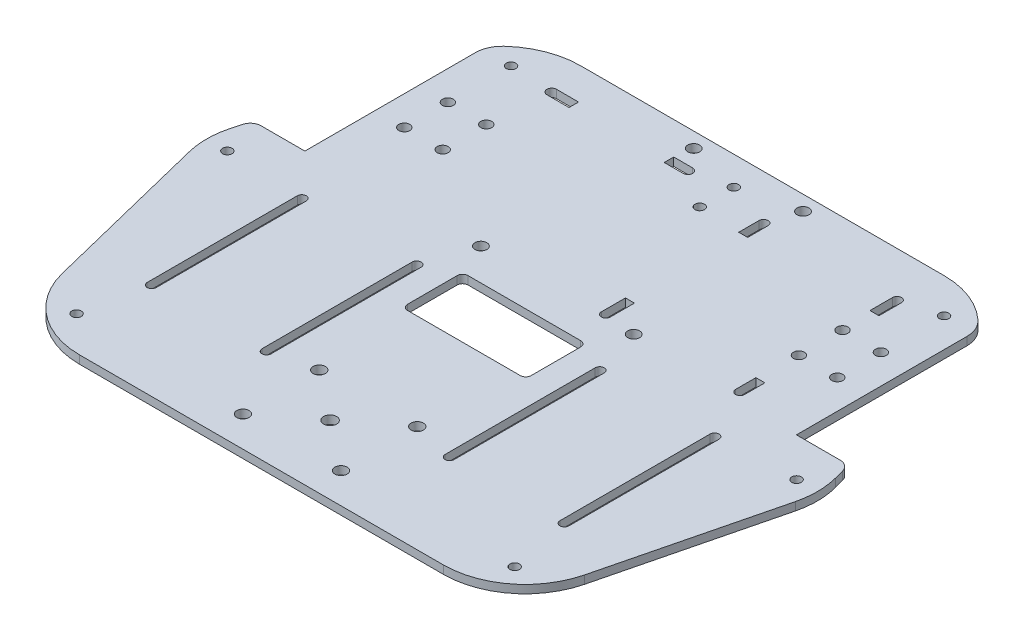
SolidWorks part; units mm, degrees
ref_plane "前视基准面" through (0, 0, 0) normal (0, 0, 1) x (1, 0, 0)
ref_plane "上视基准面" through (0, 0, 0) normal (0, 1, 0) x (1, 0, 0)
ref_plane "右视基准面" through (0, 0, 0) normal (1, 0, 0) x (0, 0, -1)
sketch "草图1" plane through (0, 0, 0) normal (0, 1, 0) x (1, 0, 0)
  line L0 (0, 115.8486) -> (0, -4.1514) construction
  line L1 (-90.25, 115.8486) -> (90.25, 115.8486) construction
  line L2 (96.25, 148.3486) -> (96.25, 83.3486) construction
  line L3 (90.25, 115.8486) -> (96.25, 115.8486) construction
  line L4 (-90.25, 115.8486) -> (-96.25, 115.8486) construction
  line L5 (-96.25, 148.3486) -> (-96.25, 83.3486) construction
  line L6 (90.25, 115.8486) -> (90.25, 131.8486)
  line L7 (95.8987, -6.5662) -> (111.2655, 55.4037)
  line L9 (-95.8987, -6.5662) -> (-111.2655, 55.4037)
  line L10 (137.9048, 62.6242) -> (-113.2043, 62.6242) construction
  line L11 (-90.25, 83.3486) -> (-90.25, 131.8486)
  line L12 (-66.7806, -29.3457) -> (66.7806, -29.3457)
  line L13 (90.25, 83.3486) -> (90.25, 76.8314)
  line L14 (-90.25, 83.3486) -> (-90.25, 76.8314)
  line L15 (-110.1941, 73.8661) -> (-111.1265, 70.3839)
  line L16 (90.25, 83.3486) -> (90.25, 115.8486)
  line L17 (110.1941, 73.8661) -> (111.1265, 70.3839)
  line L18 (106.3302, 76.8314) -> (90.25, 76.8314)
  line L19 (-90.25, 76.8314) -> (-106.3302, 76.8314)
  line L20 (0, 9.3997) -> (0, 129.3997) construction
  line L21 (-66.7806, 154.594) -> (66.7806, 154.594)
  line L22 (-90.25, 131.8486) -> (-90.25, 139.3783)
  line L23 (90.25, 131.8486) -> (90.25, 139.3783)
  arc A0 (95.8987, -6.5662) -> (66.7806, -29.3457) centre (66.7806, 0.6543) cw
  arc A1 (-66.7806, -29.3457) -> (-95.8987, -6.5662) centre (-66.7806, 0.6543) cw
  arc A2 (111.2655, 55.4037) -> (111.1265, 70.3839) centre (82.1474, 62.6242) ccw
  arc A3 (-111.1265, 70.3839) -> (-111.2655, 55.4037) centre (-82.1474, 62.6242) ccw
  circle A4 centre (0, -4.1514) radius 2.4148
  arc A5 (90.25, 139.3783) -> (86.9847, 146.7704) centre (80.25, 139.3783) ccw
  arc A6 (-66.7806, 154.594) -> (-86.9847, 146.7704) centre (-66.7806, 124.594) ccw
  arc A7 (86.9847, 146.7704) -> (66.7806, 154.594) centre (66.7806, 124.594) ccw
  arc A8 (-86.9847, 146.7704) -> (-90.25, 139.3783) centre (-80.25, 139.3783) ccw
  arc A9 (110.1941, 73.8661) -> (106.3302, 76.8314) centre (106.3302, 72.8314) ccw
  arc A10 (-106.3302, 76.8314) -> (-110.1941, 73.8661) centre (-106.3302, 72.8314) ccw
  point P6 (0, 115.8486)
  point P10 (96.25, 115.8486)
  point P18 (90.25, -29.3457)
  point P24 (-90.25, -29.3457)
  point P26 (0, 62.6242)
  point P28 (113.2043, 62.6242)
  point P51 (-90.25, 154.594)
  point P52 (90.25, 154.594)
  dimension "D5" = 30
  dimension "D6" = 30
  dimension "D8" = 10
  dimension "D9" = 4
  dimension "D1" = 180.5
  dimension "D2" = 120
  dimension "D3" = 65
  dimension "D4" = 6
  dimension "D7" = 16
extrude "凸台-拉伸1" add sketch "草图1" along normal blind 3
sketch "草图2" plane through (0, 3, 0) normal (0, 1, 0) x (1, 0, 0)
  line L0 (85.2655, -22.9742) -> (66.7806, 0.6543) construction
  line L1 (0, 85.1711) -> (0, 26.2624) construction
  line L2 (-85.2655, -22.9742) -> (-66.7806, 0.6543) construction
  arc A0 (66.7806, -29.3457) -> (95.8987, -6.5662) centre (66.7806, 0.6543) ccw construction
  circle A1 centre (80.4502, -16.819) radius 1.75
  circle A2 centre (104.5075, 62.6242) radius 1.75
  circle A3 centre (-104.5075, 62.6242) radius 1.75
  circle A4 centre (-80.4502, -16.819) radius 1.75
  dimension "D1" = 3.5
  dimension "D2" = 3.5
extrude "切除-拉伸1" cut sketch "草图2" against normal blind 10
sketch "草图3" plane through (0, 3, 0) normal (0, 1, 0) x (1, 0, 0)
  circle A0 centre (0, 131.5682) radius 1.75 construction
  circle A1 centre (0, 144.0797) radius 1.75 construction
  circle A2 centre (0, 131.5682) radius 1.75
  circle A3 centre (0, 144.0797) radius 1.75
extrude "切除-拉伸2" cut sketch "草图3" against normal blind 10
sketch "草图4" plane through (0, 0, 0) normal (0, -1, 0) x (1, 0, 0)
  circle A0 centre (79.5, -102.5986) radius 2
  circle A1 centre (65.4, -102.5986) radius 2
  circle A2 centre (65.4, -118.5986) radius 2
  circle A3 centre (79.5, -118.5986) radius 2
  circle A4 centre (-65.4, -102.5986) radius 2
  circle A5 centre (-79.5, -102.5986) radius 2
  circle A6 centre (-79.5, -118.5986) radius 2
  circle A7 centre (-65.4, -118.5986) radius 2
  dimension "D1" = 4
extrude "切除-拉伸3" cut sketch "草图4" against normal blind 10
sketch "草图5" plane through (0, 3, 0) normal (0, 1, 0) x (1, 0, 0)
  circle A0 centre (28.3878, 78.9331) radius 2.1871 construction
  circle A1 centre (-27.7186, 78.9331) radius 2.1871 construction
  circle A2 centre (20.3846, 149.1149) radius 2.1871 construction
  circle A3 centre (-19.6955, 149.0549) radius 2.1871 construction
  circle A4 centre (28.3878, 78.9331) radius 2.1871
  circle A5 centre (-27.7186, 78.9331) radius 2.1871
  circle A6 centre (20.3846, 149.1149) radius 2.1871
  circle A7 centre (-19.6955, 149.0549) radius 2.1871
extrude "切除-拉伸4" cut sketch "草图5" against normal blind 10
sketch "草图6" plane through (0, 3, 0) normal (0, 1, 0) x (1, 0, 0)
  line L0 (0, 154.594) -> (0, 181.3556) construction
  line L1 (-66.7806, 154.594) -> (66.7806, 154.594) construction
  circle A0 centre (79.5, 141.7823) radius 1.75
  circle A1 centre (-79.5, 141.7823) radius 1.75
  dimension "D1" = 3.5
extrude "切除-拉伸5" cut sketch "草图6" against normal blind 10
sketch "草图7" plane through (0, 3, 0) normal (0, 1, 0) x (1, 0, 0)
  line L0 (41.6109, 138.15) -> (41.6109, 54.7756) construction
  line L1 (67.9139, 80.1501) -> (67.9139, 87.5882)
  line L2 (67.9139, 87.5882) -> (64.6139, 87.5882)
  line L3 (64.6139, 87.5882) -> (64.6139, 80.1501)
  line L4 (18.5182, 138.15) -> (18.5182, 130.6663)
  line L5 (18.5182, 130.6663) -> (15.2182, 130.6663)
  line L6 (15.2182, 130.6663) -> (15.2182, 138.15)
  line L7 (18.608, 80.1501) -> (18.608, 88.9939)
  line L8 (18.608, 88.9939) -> (15.308, 88.9939)
  line L9 (15.308, 88.9939) -> (15.308, 80.1501)
  line L10 (64.2182, 138.15) -> (64.2182, 129.8668)
  line L11 (64.2182, 129.8668) -> (67.5182, 129.8668)
  line L12 (67.5182, 129.8668) -> (67.5182, 138.15)
  arc A0 (67.5182, 138.15) -> (64.2182, 138.15) centre (65.8682, 138.15) ccw
  arc A1 (18.5182, 138.15) -> (15.2182, 138.15) centre (16.8682, 138.15) ccw
  arc A2 (15.308, 80.1501) -> (18.608, 80.1501) centre (16.958, 80.1501) ccw
  arc A3 (67.9139, 80.1501) -> (64.6139, 80.1501) centre (66.2639, 80.1501) cw
  dimension "D1" = 3.3
  dimension "D2" = 3.3
  dimension "D3" = 49
  dimension "D4" = 3.3
  dimension "D5" = 58
extrude "切除-拉伸6" cut sketch "草图7" against normal blind 10
sketch "草图8" plane through (0, 3, 0) normal (0, 1, 0) x (1, 0, 0)
  line L0 (-63.7186, 140.9246) -> (-13.7186, 140.9246) construction
  line L1 (-63.7186, 139.1746) -> (-55.5968, 139.1746)
  line L2 (-13.7186, 142.6746) -> (-20.6494, 142.6746)
  line L3 (-55.5968, 142.6746) -> (-55.5968, 139.1746)
  line L4 (-20.6494, 142.6746) -> (-20.6494, 139.1746)
  line L5 (-55.5968, 142.6746) -> (-63.7186, 142.6746)
  line L6 (-20.6494, 139.1746) -> (-13.7186, 139.1746)
  arc A0 (-13.7186, 139.1746) -> (-13.7186, 142.6746) centre (-13.7186, 140.9246) ccw
  arc A1 (-63.7186, 142.6746) -> (-63.7186, 139.1746) centre (-63.7186, 140.9246) ccw
  dimension "D3" = 3.5
  dimension "D1" = 50
extrude "切除-拉伸7" cut sketch "草图8" against normal blind 10
sketch "草图9" plane through (0, 3, 0) normal (0, 1, 0) x (1, 0, 0)
  line L1 (-20.6886, 67.1866) -> (20.6886, 67.1866)
  line L2 (-22.6886, 65.1866) -> (-22.6886, 46.9912)
  line L3 (-20.6886, 44.9912) -> (20.6886, 44.9912)
  line L4 (22.6886, 65.1866) -> (22.6886, 46.9912)
  line L5 (-22.6886, 67.1866) -> (22.6886, 44.9912) construction
  line L6 (-22.6886, 44.9912) -> (22.6886, 67.1866) construction
  arc A0 (20.6886, 67.1866) -> (22.6886, 65.1866) centre (20.6886, 65.1866) cw
  arc A1 (-22.6886, 46.9912) -> (-20.6886, 44.9912) centre (-20.6886, 46.9912) ccw
  arc A2 (-20.6886, 67.1866) -> (-22.6886, 65.1866) centre (-20.6886, 65.1866) ccw
  arc A3 (20.6886, 44.9912) -> (22.6886, 46.9912) centre (20.6886, 46.9912) ccw
  point P0 (0, 56.0889)
  dimension "D1" = 2
extrude "切除-拉伸8" cut sketch "草图9" against normal blind 10
sketch "草图11" plane through (0, 3, 0) normal (0, 1, 0) x (1, 0, 0)
  line L0 (-75.7783, 61.2346) -> (-75.7783, 6.1219) construction
  line L1 (-74.1283, 61.2346) -> (-74.1283, 6.1219)
  line L2 (-77.4283, 61.2346) -> (-77.4283, 6.1219)
  line L3 (0, 78.4105) -> (0, -70.8209) construction
  line L4 (-33.6189, 61.2346) -> (-33.6189, 6.1219) construction
  line L5 (-31.9689, 61.2346) -> (-31.9689, 6.1219)
  line L6 (-35.2689, 61.2346) -> (-35.2689, 6.1219)
  line L7 (33.6189, 61.2346) -> (33.6189, 6.1219) construction
  line L8 (31.9689, 61.2346) -> (31.9689, 6.1219)
  line L9 (35.2689, 61.2346) -> (35.2689, 6.1219)
  line L10 (75.7783, 61.2346) -> (75.7783, 6.1219) construction
  line L11 (74.1283, 61.2346) -> (74.1283, 6.1219)
  line L12 (77.4283, 61.2346) -> (77.4283, 6.1219)
  arc A0 (-74.1283, 61.2346) -> (-77.4283, 61.2346) centre (-75.7783, 61.2346) ccw
  arc A1 (-77.4283, 6.1219) -> (-74.1283, 6.1219) centre (-75.7783, 6.1219) ccw
  arc A2 (-31.9689, 61.2346) -> (-35.2689, 61.2346) centre (-33.6189, 61.2346) ccw
  arc A3 (-35.2689, 6.1219) -> (-31.9689, 6.1219) centre (-33.6189, 6.1219) ccw
  arc A4 (31.9689, 61.2346) -> (35.2689, 61.2346) centre (33.6189, 61.2346) cw
  arc A5 (35.2689, 6.1219) -> (31.9689, 6.1219) centre (33.6189, 6.1219) cw
  arc A6 (74.1283, 61.2346) -> (77.4283, 61.2346) centre (75.7783, 61.2346) cw
  arc A7 (77.4283, 6.1219) -> (74.1283, 6.1219) centre (75.7783, 6.1219) cw
  point P2 (-75.7783, 33.6783)
  point P12 (-33.6189, 33.6783)
  point P19 (33.6189, 33.6783)
  point P26 (75.7783, 33.6783)
  dimension "D1" = 1.65
extrude "切除-拉伸9" cut sketch "草图11" against normal blind 10
sketch "草图12" plane through (0, 0, 0) normal (0, -1, 0) x (1, 0, 0)
  line L0 (0, 4.1514) -> (18, 4.1514) construction
  line L1 (18, 4.1514) -> (18, 18.1514) construction
  line L2 (0, 4.1514) -> (0, 12.7899) construction
  circle A0 centre (18, 18.1514) radius 2.25
  circle A1 centre (18, -9.8486) radius 2.25
  circle A2 centre (-18, 18.1514) radius 2.25
  circle A3 centre (-18, -9.8486) radius 2.25
  dimension "D3" = 4.5
  dimension "D1" = 18
  dimension "D2" = 14
extrude "切除-拉伸10" cut sketch "草图12" against normal blind 10
